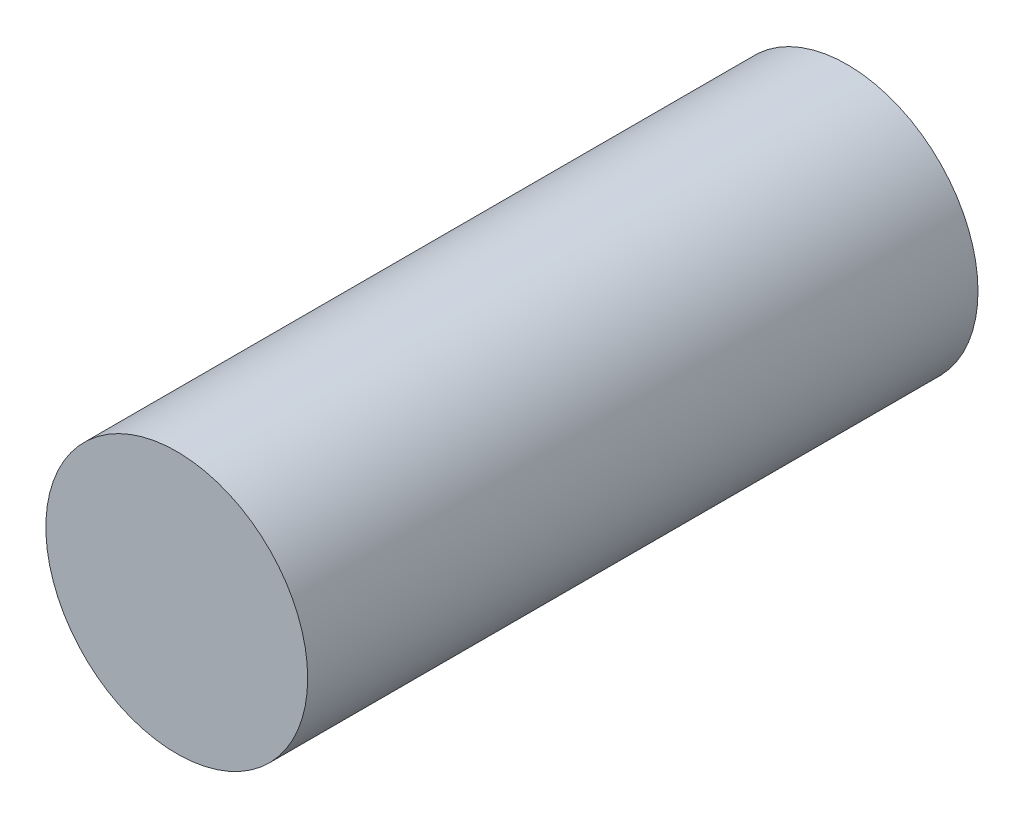
SolidWorks part; units mm, degrees
ref_plane "Front Plane" through (0, 0, 0) normal (0, 0, 1) x (1, 0, 0)
ref_plane "Top Plane" through (0, 0, 0) normal (0, 1, 0) x (1, 0, 0)
ref_plane "Right Plane" through (0, 0, 0) normal (1, 0, 0) x (0, 0, -1)
sketch "Sketch1" plane through (0, 0, 0) normal (0, 0, 1) x (1, 0, 0)
  circle A0 centre (0, 0) radius 12.5
  dimension "D1" = 25
extrude "Boss-Extrude1" add sketch "Sketch1" along normal blind 64
